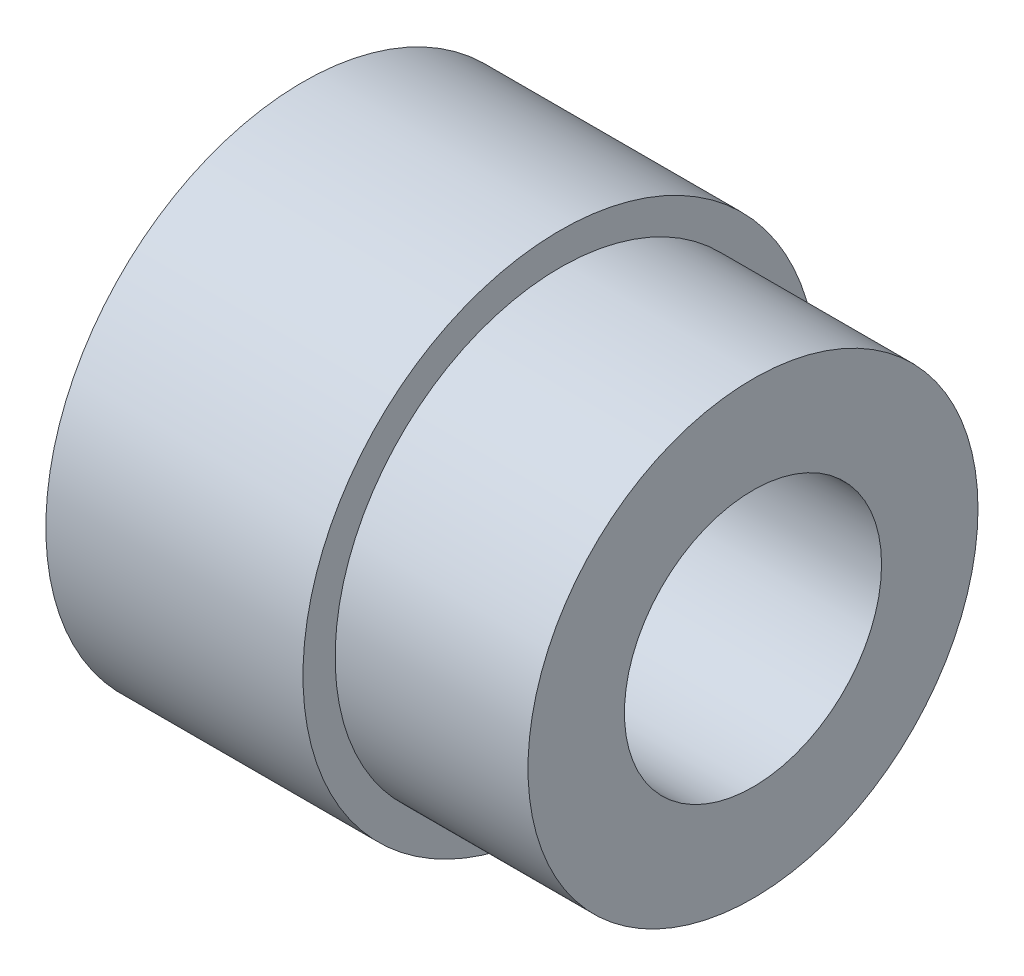
SolidWorks part; units mm, degrees
ref_plane "Front Plane" through (0, 0, 0) normal (0, 0, 1) x (1, 0, 0)
ref_plane "Top Plane" through (0, 0, 0) normal (0, 1, 0) x (1, 0, 0)
ref_plane "Right Plane" through (0, 0, 0) normal (1, 0, 0) x (0, 0, -1)
sketch "Sketch1" plane through (0, 0, 0) normal (1, 0, 0) x (0, 0, -1)
  circle A0 centre (0, 0) radius 2
extrude "Boss-Extrude1" add sketch "Sketch1" along normal blind 2
sketch "Sketch2" plane through (2, 0, 0) normal (1, 0, 0) x (0, 0, -1)
  circle A0 centre (0, 0) radius 1.75
extrude "Boss-Extrude2" add sketch "Sketch2" along normal blind 1.5
sketch "Sketch3" plane through (3.5, 0, 0) normal (1, 0, 0) x (0, 0, -1)
  circle A0 centre (0, 0) radius 1
extrude "Cut-Extrude1" cut sketch "Sketch3" against normal blind 11.5
